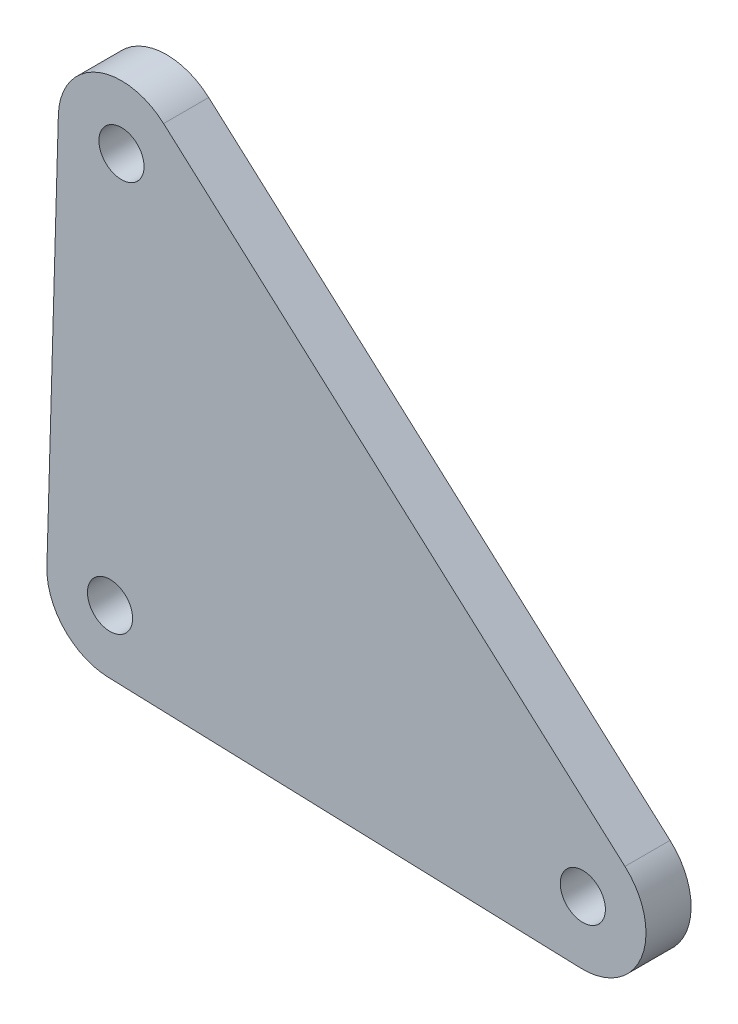
SolidWorks part; units mm, degrees
ref_plane "Front Plane" through (0, 0, 0) normal (0, 0, 1) x (1, 0, 0)
ref_plane "Top Plane" through (0, 0, 0) normal (0, 1, 0) x (1, 0, 0)
ref_plane "Right Plane" through (0, 0, 0) normal (1, 0, 0) x (0, 0, -1)
sketch "Sketch1" plane through (0, 0, 0) normal (0, 0, 1) x (1, 0, 0)
  line L1 (0, 0) -> (1.613, 55.88) construction
  line L7 (1.613, 55.88) -> (66.548, -2.2034) construction
  line L8 (66.548, -2.2034) -> (0, 0) construction
  line L9 (-9.1417, -8.5922) -> (-6.7213, 75.2624)
  line L10 (-6.7213, 75.2624) -> (90.7215, -11.8987)
  line L11 (90.7215, -11.8987) -> (-9.1417, -8.5922)
  circle A0 centre (1.613, 55.88) radius 3.175
  circle A1 centre (0, 0) radius 3.175
  circle A2 centre (66.548, -2.2034) radius 3.175
  dimension "D3" = 55.88
  dimension "D4" = 6.35
  dimension "D1" = 87.122
  dimension "D2" = 66.548
  dimension "D5" = 8.89
extrude "Boss-Extrude1" add sketch "Sketch1" along normal blind 6.35
fillet "Fillet1" radius 8.89 3 edges at (90.7215, -11.8987, 3.175) (-9.1417, -8.5922, 3.175) (-6.7213, 75.2624, 3.175)
